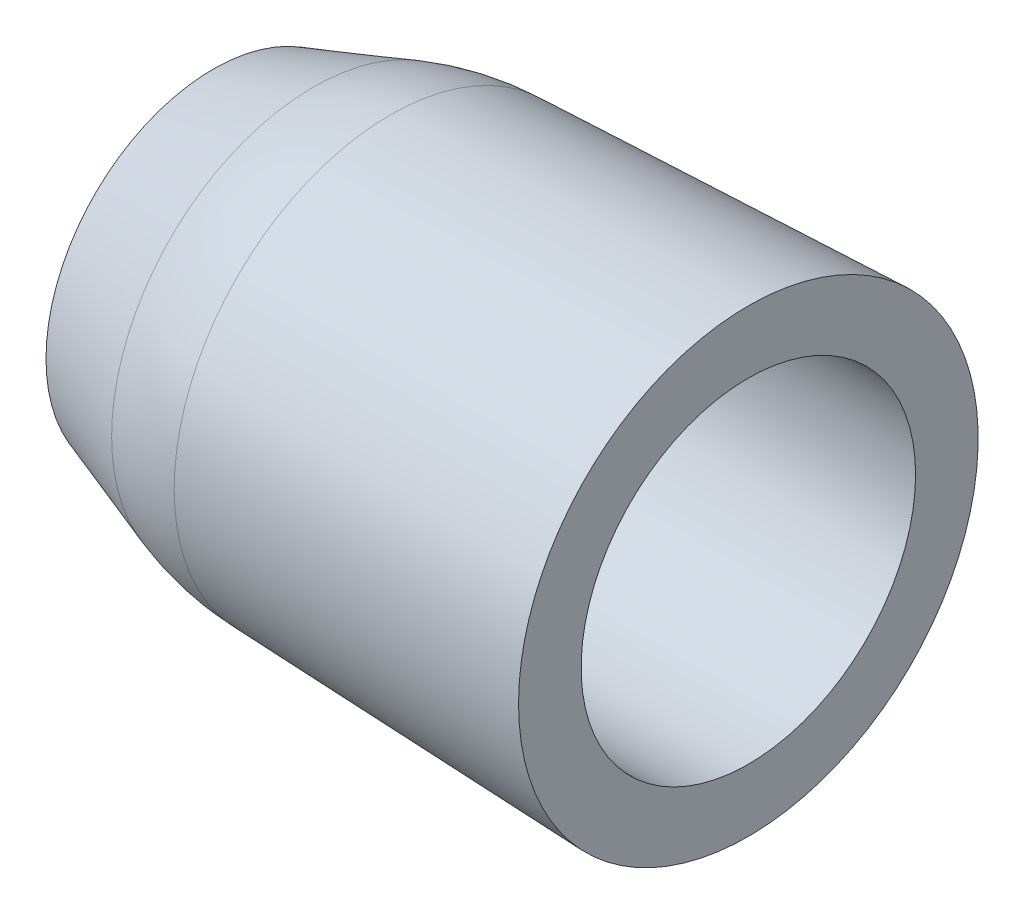
SolidWorks part; units mm, degrees
material "ABS"
ref_plane "Front Plane" through (0, 0, 0) normal (0, 0, 1) x (1, 0, 0)
ref_plane "Top Plane" through (0, 0, 0) normal (0, 1, 0) x (1, 0, 0)
ref_plane "Right Plane" through (0, 0, 0) normal (1, 0, 0) x (0, 0, -1)
sketch "Sketch2" plane through (0, 0, 0) normal (0, 0, 1) x (1, 0, 0)
  line L0 (-27.8095, 0) -> (-2.4095, 0) construction
  line L1 (-2.4095, 10.9078) -> (-21.2812, 10.1867)
  line L2 (-21.2812, 10.1867) -> (-27.8095, 7.9375)
  line L3 (-27.8095, 7.9375) -> (-27.8095, 0)
  line L4 (-2.4095, 10.9078) -> (-2.4095, 0)
  line L5 (-27.8095, 0) -> (-2.4095, 0)
  line L6 (-27.8095, 0) -> (-2.4095, 0)
  dimension "D1" = 7.9375
  dimension "D2" = 25.4
revolve "Revolve1" add sketch "Sketch2" angle 360 about L0
sketch "Sketch3" plane through (-2.4095, 0, 0) normal (1, 0, 0) x (0, 0, -1)
  circle A0 centre (0, 0) radius 7.9375
  dimension "D1" = 15.875
extrude "Cut-Extrude1" cut sketch "Sketch3" against normal blind 25.146
fillet "Fillet1" radius 12.7 1 edges at (-21.2812, 0, 10.1867)
